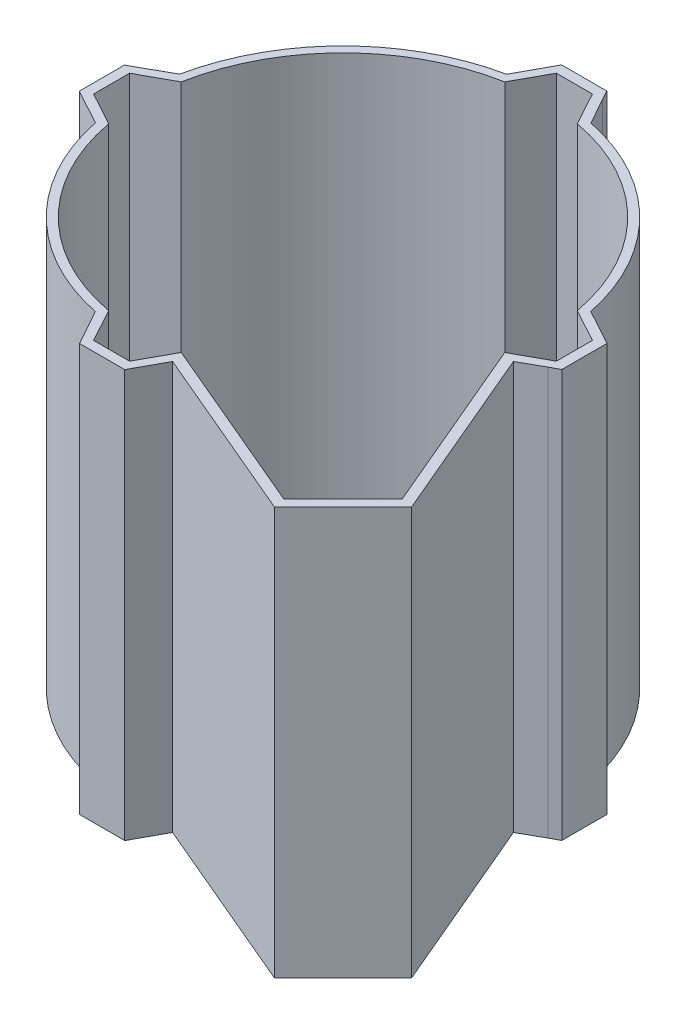
SolidWorks part; units mm, degrees
ref_plane "Alzado" through (0, 0, 0) normal (0, 0, 1) x (1, 0, 0)
ref_plane "Planta" through (0, 0, 0) normal (0, 1, 0) x (1, 0, 0)
ref_plane "Vista lateral" through (0, 0, 0) normal (1, 0, 0) x (0, 0, -1)
sketch "Croquis1" plane through (0, 0, 0) normal (0, 1, 0) x (1, 0, 0)
  line L0 (4, 58) -> (8.8071, 49.2182)
  line L1 (-4, 58) -> (4, 58)
  line L7 (-4, 58) -> (-8.8071, 49.2182)
  line L8 (58, 4) -> (58, -4)
  line L9 (58, 4) -> (49.2182, 8.8071)
  line L10 (58, -4) -> (49.2182, -8.8071)
  line L11 (4, -58) -> (-4, -58)
  line L12 (4, -58) -> (8.8071, -49.2182)
  line L13 (-4, -58) -> (-8.8071, -49.2182)
  line L14 (-58, -4) -> (-58, 4)
  line L15 (-58, -4) -> (-49.2182, -8.8071)
  line L16 (-58, 4) -> (-49.2182, 8.8071)
  arc A0 (-8.8071, 49.2182) -> (-49.2182, 8.8071) centre (0, 0) ccw
  arc A1 (-49.2182, -8.8071) -> (-8.8071, -49.2182) centre (0, 0) ccw
  arc A2 (49.2182, 8.8071) -> (8.8071, 49.2182) centre (0, 0) ccw
  arc A3 (8.8071, -49.2182) -> (49.2182, -8.8071) centre (0, 0) ccw
  point P3 (0, 50)
  point P25 (0, 0)
  dimension "D1" = 100
  dimension "D3" = 8
  dimension "D4" = 4
extrude "Saliente-Extruir1" add sketch "Croquis1" along normal blind 5
sketch "Croquis2" plane through (0, 5, 0) normal (0, 1, 0) x (1, 0, 0)
  line L0 (4, 58) -> (-4, 58) construction
  circle A0 centre (0, 52.7) radius 2.1
  circle A1 centre (52.7, 0) radius 2.1
  circle A2 centre (0, -52.7) radius 2.1
  circle A3 centre (-52.7, 0) radius 2.1
  point P13 (0, 0)
  dimension "D1" = 4.2
  dimension "D2" = 5.3
  dimension "D4" = 0
  dimension "D3" = 4
extrude "Cortar-Extruir1" cut sketch "Croquis2" against normal through all
cosmetic thread "Rosca cosmética5" parameters "D2"=5
cosmetic thread "Rosca cosmética6" parameters "D2"=5
cosmetic thread "Rosca cosmética7" parameters "D2"=5
cosmetic thread "Rosca cosmética8" parameters "D2"=5
sketch "Croquis3" plane through (0, 5, 0) normal (0, 1, 0) x (1, 0, 0)
  line L0 (0, 0) -> (33.9411, -33.9411) construction
  line L11 (20.5061, -34.6482) -> (34.6482, -20.5061)
  line L16 (20.5061, -34.6482) -> (33.234, -47.3762)
  line L23 (34.6482, -20.5061) -> (47.3762, -33.234)
  line L24 (20.5061, -34.6482) -> (47.3762, -33.234) construction
  line L25 (33.234, -47.3762) -> (34.6482, -20.5061) construction
  line L27 (33.234, -47.3762) -> (53.0768, -67.2189)
  line L28 (53.0768, -67.2189) -> (67.2189, -53.0768)
  line L29 (47.3762, -33.234) -> (67.2189, -53.0768)
  point P224 (33.9411, -56.9721)
  point P274 (21.2132, -31.2132)
  point P609 (21.2132, -48.2132)
  dimension "D1" = 18
  dimension "D2" = 20
  dimension "D3" = 48
extrude "Cortar-Extruir2" cut sketch "Croquis3" against normal through all
sketch "Croquis5" plane through (0, 5, 0) normal (0, 1, 0) x (1, 0, 0)
  line L9 (21.5541, -30.0393) -> (23.3345, -31.8198)
  line L11 (28.6251, -22.9683) -> (30.9862, -25.3293)
  line L12 (30.9862, -25.3293) -> (32.4004, -23.9151)
  line L13 (30.0393, -21.5541) -> (32.4004, -23.9151)
  line L14 (29.7686, -22.1503) -> (32.4004, -23.9151) construction
  line L15 (30.9862, -25.3293) -> (29.2214, -22.6975) construction
  line L17 (22.9683, -28.6251) -> (24.7487, -30.4056)
  line L20 (34.6482, -20.5061) -> (20.5061, -34.6482) construction
  line L21 (23.3345, -31.8198) -> (24.7487, -30.4056)
  line L22 (20.5061, -34.6482) -> (27.5699, -41.7121) construction
  line L23 (41.7121, -27.5699) -> (34.6482, -20.5061) construction
  circle A1 centre (-7.78, 7.78) radius 2.05
  circle A2 centre (7.78, 7.78) radius 2.05
  circle A3 centre (7.78, -7.78) radius 2.05
  circle A4 centre (-7.78, -7.78) radius 2.05
  arc A5 (30.0393, -21.5541) -> (28.6251, -22.9683) centre (28.1075, -21.0364) ccw
  arc A6 (22.9683, -28.6251) -> (21.5541, -30.0393) centre (21.0364, -28.1075) ccw
  point P13 (0, 0)
  dimension "D1" = 4.1
  dimension "D5" = 4
  dimension "D6" = 4
  dimension "D2" = 7.78
  dimension "D3" = 7.78
  dimension "D7" = 4.25
  dimension "D8" = 4.25
  dimension "D9" = 5
  dimension "D10" = 5
  dimension "D12" = 2
  dimension "D4" = 4
extrude "Cortar-Extruir4" cut sketch "Croquis5" against normal through all
cosmetic thread "Rosca cosmética1" parameters "D2"=5
cosmetic thread "Rosca cosmética2" parameters "D2"=5
cosmetic thread "Rosca cosmética3" parameters "D2"=5
cosmetic thread "Rosca cosmética4" parameters "D2"=5
sketch "Croquis7" plane through (0, 5, 0) normal (0, 1, 0) x (1, 0, 0)
  line L6 (68.5894, -54.4472) -> (54.4472, -68.5894)
  line L7 (48.7904, -62.9325) -> (62.9325, -48.7904)
  line L8 (68.5894, -54.4472) -> (49.2182, -8.8071)
  line L9 (34.6482, -20.5061) -> (31.8198, -23.3345) construction
  line L10 (48.7904, -62.9325) -> (27.5699, -41.7121)
  line L11 (62.9325, -48.7904) -> (41.7121, -27.5699)
  line L12 (41.7121, -27.5699) -> (46.423, -18.5717)
  line L13 (27.5699, -41.7121) -> (18.5717, -46.423)
  line L14 (49.2182, -8.8071) -> (46.423, -18.5717)
  line L15 (54.4472, -68.5894) -> (8.8071, -49.2182)
  line L16 (8.8071, -49.2182) -> (18.5717, -46.423)
  arc A0 (41.7121, -27.5699) -> (49.2182, -8.8071) centre (0, 0) ccw construction
  arc A1 (8.8071, -49.2182) -> (27.5699, -41.7121) centre (0, 0) ccw construction
  dimension "D1" = 8
  dimension "D2" = 40
extrude "Saliente-Extruir2" add sketch "Croquis7" against normal through all
sketch "Croquis8" plane through (0, 5, 0) normal (0, 1, 0) x (1, 0, 0)
  line L0 (62.9325, -48.7904) -> (48.7904, -62.9325) construction
  line L5 (54.2831, -59.94) -> (51.4902, -57.1471)
  line L6 (51.4902, -57.1471) -> (50.076, -58.5613)
  line L8 (55.8008, -67.5537) -> (55.1474, -63.8416) construction
  line L9 (55.8008, -56.19) -> (55.1474, -59.9021) construction
  line L11 (57.3718, -51.715) -> (58.7861, -50.3008)
  line L12 (57.3718, -51.715) -> (59.94, -54.2831)
  line L14 (58.7861, -50.3008) -> (61.3542, -52.8689)
  line L15 (54.4541, -59.9021) -> (53.8008, -56.19) construction
  line L18 (54.4541, -63.8416) -> (53.8008, -67.5537) construction
  line L19 (52.8689, -61.3542) -> (50.076, -58.5613)
  line L21 (62.9325, -48.7904) -> (48.7904, -62.9325) construction
  arc A3 (59.94, -54.2831) -> (61.3542, -52.8689) centre (61.8718, -54.8008) ccw
  arc A6 (52.8689, -61.3542) -> (54.2831, -59.94) centre (54.8008, -61.8718) ccw
  dimension "D1" = 4
  dimension "D3" = 3.5
  dimension "D4" = 3.5
  dimension "D7" = 2
  dimension "D8" = 2
extrude "Cortar-Extruir10" cut sketch "Croquis8" against normal through all
sketch "Croquis15" plane through (0, 0, 0) normal (0, -1, 0) x (1, 0, 0)
  line L2 (-1.1111, -20.4699) -> (-1.1111, -22.4725)
  line L4 (1.1111, -20.4699) -> (1.1111, -22.4725)
  arc A0 (1.1111, -22.4725) -> (-1.1111, -22.4725) centre (0, 0) ccw
  arc A1 (1.1111, -20.4699) -> (-1.1111, -20.4699) centre (0, 0) ccw
  point P4 (0, -19.25)
  dimension "D1" = 45
  dimension "D2" = 41
  dimension "D4" = 19.25
  dimension "D5" = 0
extrude "Saliente-Extruir4" add sketch "Croquis15" along normal blind 4
sketch "Croquis16" plane through (0, 0, 0) normal (0, -1, 0) x (1, 0, 0)
  line L0 (1.1111, -20.4699) -> (1.1111, -22.4725) construction
  line L1 (-1.1111, -20.4699) -> (-1.1111, -22.4725)
  line L2 (1.1111, -20.4699) -> (1.1111, -22.4725)
  arc A0 (-1.1111, -22.4725) -> (1.1111, -22.4725) centre (0, 0) ccw
  arc A1 (1.1111, -22.4725) -> (-1.1111, -22.4725) centre (0, 0) ccw construction
  arc A2 (-1.1111, -20.4699) -> (1.1111, -20.4699) centre (0, 0) ccw
extrude "Saliente-Extruir5" add sketch "Croquis16" along normal blind 4
sketch "Croquis17" plane through (0, 0, 0) normal (0, -1, 0) x (1, 0, 0)
  line L2 (0, 0) -> (42.43, 0) construction
  circle A2 centre (42.43, 0) radius 2.4
  circle A3 centre (0, -42.43) radius 2.4
  circle A4 centre (-42.43, 0) radius 2.4
  circle A5 centre (0, 42.43) radius 2.4
  point P13 (0, 0)
  dimension "D1" = 42.43
  dimension "D2" = 4
  dimension "D4" = 4.8
extrude "Cortar-Extruir11" cut sketch "Croquis17" against normal through all
sketch "Croquis18" plane through (0, 5, 0) normal (0, 1, 0) x (1, 0, 0)
  line L0 (61.5183, -61.5183) -> (-35.3553, 35.3553) construction
  line L1 (54.4472, -68.5894) -> (68.5894, -54.4472) construction
  line L2 (8.8071, -49.2182) -> (54.4472, -68.5894) construction
  line L3 (54.4472, -68.5894) -> (74.2597, -76.9984) construction
  line L4 (-4.4778, 59) -> (4.4778, 59)
  line L6 (5.0283, 57.9936) -> (9.3256, 50.1372) construction
  line L7 (0, 58) -> (0, 59) construction
  line L8 (4, 58) -> (-4, 58) construction
  line L9 (61.5183, -61.5183) -> (62.2254, -62.2254) construction
  line L10 (5.0283, 57.9936) -> (9.3256, 50.1372)
  line L12 (5.0283, 57.9936) -> (4.4778, 59)
  line L13 (4.4778, 59) -> (9.3256, 50.1372)
  line L14 (-4.4778, 59) -> (-9.3043, 50.1441)
  line L15 (59.0123, 4.481) -> (50.1388, 9.3171)
  line L16 (59.0123, 4.481) -> (59.0123, -4.4746)
  line L17 (58.006, -5.0251) -> (59.0123, -4.4746)
  line L18 (58.006, -5.0251) -> (50.4529, -9.1565)
  line L19 (69.7734, -54.6774) -> (54.6774, -69.7734)
  line L20 (4.4933, -59.0092) -> (9.1565, -50.4529)
  line L21 (4.4933, -59.0092) -> (-4.4623, -59.0092)
  line L22 (-5.0128, -58.0028) -> (-4.4623, -59.0092)
  line L23 (-5.0128, -58.0028) -> (-9.3121, -50.1426)
  line L24 (8.8071, -49.2182) -> (74.8349, -77.2425) construction
  line L25 (-58.9968, -4.4901) -> (-50.1419, -9.3161)
  line L26 (-58.9968, -4.4901) -> (-58.9968, 4.4655)
  line L27 (-57.9905, 5.0159) -> (-58.9968, 4.4655)
  line L28 (-57.9905, 5.0159) -> (-50.1434, 9.3082)
  line L29 (31.6271, -58.9038) -> (31.2364, -59.8243) construction
  line L30 (-7.0262, 59.1808) -> (-10.7128, 52.4165)
  line L31 (0, 59) -> (0, 61.5) construction
  line L32 (5.7622, 61.5) -> (-5.7622, 61.5)
  line L33 (-7.0262, 59.1808) -> (-5.7622, 61.5)
  line L34 (7.0262, 59.1808) -> (10.8312, 52.3921)
  line L35 (7.0262, 59.1808) -> (5.7622, 61.5)
  line L36 (59.2043, 7.0699) -> (52.4034, 10.7764)
  line L37 (59.2043, 7.0699) -> (61.5235, 5.8059)
  line L38 (61.5235, -5.7185) -> (61.5235, 5.8059)
  line L39 (59.2043, -6.9825) -> (61.5235, -5.7185)
  line L40 (59.2043, -6.9825) -> (53.5832, -10.133)
  line L41 (7.0934, -59.1606) -> (10.133, -53.5832)
  line L42 (7.0934, -59.1606) -> (5.8294, -61.4798)
  line L43 (-5.695, -61.4798) -> (5.8294, -61.4798)
  line L44 (-6.959, -59.1606) -> (-5.695, -61.4798)
  line L45 (-6.959, -59.1606) -> (-10.7424, -52.4104)
  line L46 (-59.1371, -7.0497) -> (-52.4166, -10.7124)
  line L47 (-59.1371, -7.0497) -> (-61.4563, -5.7857)
  line L48 (-61.4563, 5.7387) -> (-61.4563, -5.7857)
  line L49 (-59.1371, 7.0027) -> (-61.4563, 5.7387)
  line L50 (-59.1371, 7.0027) -> (-52.4033, 10.777)
  line L51 (7.7955, -49.8752) -> (54.6774, -69.7734) construction
  line L52 (54.6774, -69.7734) -> (11.945, -51.6364)
  line L53 (31.2364, -59.8243) -> (30.2597, -62.1256) construction
  line L54 (62.2254, -62.2254) -> (63.9932, -63.9932) construction
  line L55 (72.7335, -55.2528) -> (55.2528, -72.7335)
  line L56 (5.4308, -51.5874) -> (55.0886, -72.6638) construction
  line L57 (10.133, -53.5832) -> (55.2528, -72.7335)
  line L58 (69.7734, -54.6774) -> (51.6364, -11.945)
  line L59 (53.5832, -10.133) -> (72.7335, -55.2528)
  line L60 (11.945, -51.6364) -> (9.1565, -50.4529)
  line L61 (51.6364, -11.945) -> (50.4529, -9.1565)
  line L62 (63.1584, -32.6929) -> (60.8571, -33.6697) construction
  arc A0 (-8.8071, 49.2182) -> (-49.2182, 8.8071) centre (0, 0) ccw construction
  arc A2 (-9.3043, 50.1441) -> (-50.1434, 9.3082) centre (0, 0) ccw
  arc A3 (-10.7128, 52.4165) -> (-52.4033, 10.777) centre (0, 0) ccw
  arc A6 (-50.1419, -9.3161) -> (-9.3121, -50.1426) centre (0, 0) ccw
  arc A7 (-52.4166, -10.7124) -> (-10.7424, -52.4104) centre (0, 0) ccw
  arc A11 (50.1388, 9.3171) -> (9.3256, 50.1372) centre (0, 0) ccw
  arc A12 (52.4034, 10.7764) -> (10.8312, 52.3921) centre (0, 0) ccw
  point P54 (0.0078, -0.0046)
  point P80 (0.0336, 0.0101)
  dimension "D1" = 102
  dimension "D2" = 107
  dimension "D12" = 53.5
  dimension "D4" = 1
  dimension "D7" = 2.5
  dimension "D3" = 1
  dimension "D9" = 1
  dimension "D10" = 2.5
  dimension "D11" = 2.5
  dimension "D6" = 2
  dimension "D5" = 4
  dimension "D8" = 4
extrude "Saliente-Extruir6" add sketch "Croquis18" along normal blind 104 contours L40 L59 L55 L57 L41 L42 L43 L44 L45 A7 L46 L47 L48 L49 L50 A3 L30 L33 L32 L35 L34 A12 L36 L37 L38 L39
sketch "Croquis23" plane through (0, -4, 0) normal (0, -1, 0) x (1, 0, 0)
  line L8 (59, -4.5926) -> (58.9589, -4.6151)
  line L10 (-4.5926, -59) -> (-4.6151, -58.9589)
  line L17 (-4.5926, 59) -> (-4.6151, 58.9589)
  line L18 (4.5926, 59) -> (4.6151, 58.9589)
  line L19 (-4.5926, 59) -> (4.5926, 59)
  line L20 (-59, 4.5926) -> (-58.9589, 4.6151)
  line L21 (59, 4.5926) -> (58.9589, 4.6151)
  line L22 (4.5926, -59) -> (4.6151, -58.9589)
  line L23 (31.2364, 59.8243) -> (57.1595, 70.8269) construction
  line L24 (72.7335, 55.2528) -> (55.2528, 72.7335) construction
  line L25 (31.2364, 59.8243) -> (9.2496, 50.4924) construction
  line L26 (-59, -4.5926) -> (-58.9589, -4.6151)
  line L27 (62.2254, 62.2254) -> (69.7734, 54.6774) construction
  line L29 (62.2254, 62.2254) -> (54.6774, 69.7734) construction
  line L30 (4.6151, 58.9589) -> (9.2496, 50.4924)
  line L31 (9.2496, 50.4924) -> (54.6774, 69.7734)
  line L32 (54.6774, 69.7734) -> (69.7734, 54.6774)
  line L33 (50.4924, 9.2496) -> (69.7734, 54.6774)
  line L34 (-4.6151, 58.9589) -> (-9.2496, 50.4924)
  line L35 (59, 4.5926) -> (59, -4.5926)
  line L36 (58.9589, 4.6151) -> (50.4924, 9.2496)
  line L37 (58.9589, -4.6151) -> (50.4924, -9.2496)
  line L38 (4.5926, -59) -> (-4.5926, -59)
  line L39 (4.6151, -58.9589) -> (9.2496, -50.4924)
  line L40 (-4.6151, -58.9589) -> (-9.2496, -50.4924)
  line L41 (-59, -4.5926) -> (-59, 4.5926)
  line L42 (-58.9589, -4.6151) -> (-50.4924, -9.2496)
  line L43 (-58.9589, 4.6151) -> (-50.4924, 9.2496)
  line L45 (9.2496, 50.4924) -> (4.5926, 59) construction
  arc A3 (-9.2496, 50.4924) -> (-50.4924, 9.2496) centre (0, 0) ccw
  arc A5 (9.2496, -50.4924) -> (50.4924, -9.2496) centre (0, 0) ccw
  arc A7 (-50.4924, -9.2496) -> (-9.2496, -50.4924) centre (0, 0) ccw
  point P12 (0, 0)
  point P19 (0, 0)
  point P87 (0, 0)
  dimension "D1" = 4
  dimension "D2" = 4
  dimension "D5" = 4
extrude "Cortar-Extruir12" cut sketch "Croquis23" against normal blind 200
